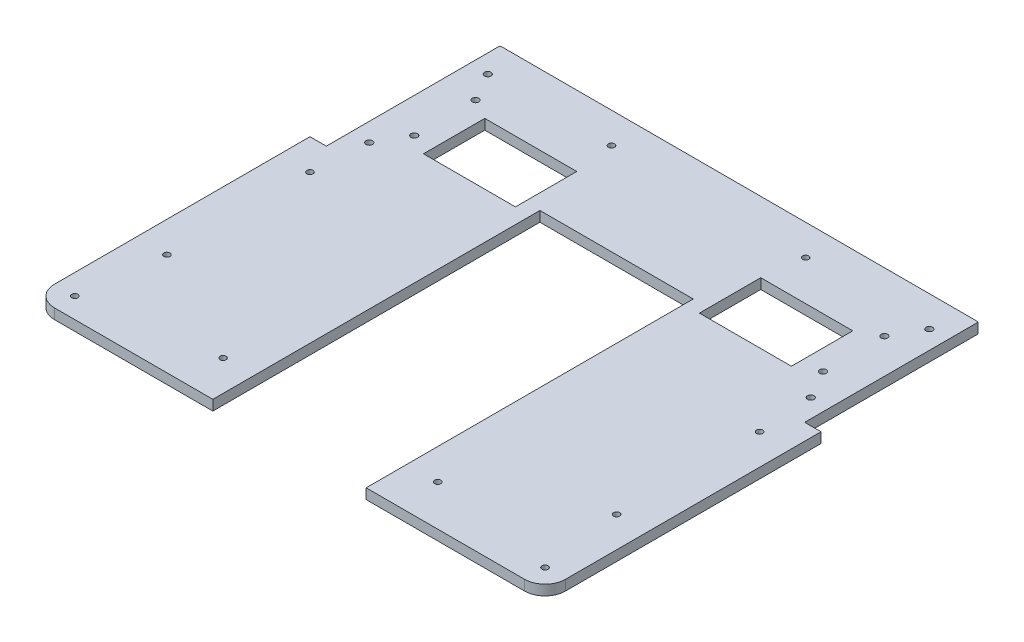
SolidWorks part; units mm, degrees
ref_plane "前视基准面" through (0, 0, 0) normal (0, 0, 1) x (1, 0, 0)
ref_plane "上视基准面" through (0, 0, 0) normal (0, 1, 0) x (1, 0, 0)
ref_plane "右视基准面" through (0, 0, 0) normal (1, 0, 0) x (0, 0, -1)
sketch "草图1" plane through (0, 0, 0) normal (0, 1, 0) x (1, 0, 0)
  line L1 (10, 0) -> (240, 0)
  line L2 (0, -10) -> (0, -210)
  line L3 (10, -220) -> (240, -220)
  line L4 (250, -10) -> (250, -210)
  arc A0 (0, -210) -> (10, -220) centre (10, -210) ccw
  arc A1 (240, -220) -> (250, -210) centre (240, -210) ccw
  arc A2 (240, 0) -> (250, -10) centre (240, -10) cw
  arc A3 (10, 0) -> (0, -10) centre (10, -10) ccw
  point P9 (250, -220)
  point P12 (250, 0)
  point P15 (0, 0)
  dimension "D3" = 10
  dimension "D1" = 250
  dimension "D2" = 220
extrude "凸台-拉伸1" add sketch "草图1" along normal blind 5
sketch "草图2" plane through (0, 0, 0) normal (0, -1, 0) x (1, 0, 0)
  line L0 (239.1778, 11.85) -> (239.1778, 76.15) construction
  line L1 (239.1778, 11.85) -> (239.1778, 76.15)
  line L2 (250, 210) -> (250, 10) construction
  line L3 (239.1778, 76.15) -> (250, 76.15)
  line L4 (239.1778, 76.15) -> (239.1778, 0)
  line L5 (239.1778, 0) -> (250, 0)
  line L6 (250, 76.15) -> (250, 0)
  line L7 (125, 220) -> (125, 0) construction
  line L8 (10, 220) -> (240, 220) construction
  line L9 (240, 0) -> (10, 0) construction
  line L10 (0, 76.15) -> (0, 0)
  line L11 (10.8222, 0) -> (0, 0)
  line L12 (10.8222, 76.15) -> (10.8222, 0)
  line L13 (10.8222, 76.15) -> (0, 76.15)
sketch "草图4" plane through (0, 0, 0) normal (0, -1, 0) x (1, 0, 0)
  line L1 (125, 0) -> (125, 220) construction
  line L2 (240, 0) -> (10, 0) construction
  line L3 (10, 220) -> (240, 220) construction
  line L8 (170, 64.475) -> (170, 34.475)
  line L16 (215, 34.475) -> (170, 34.475)
  line L17 (215, 64.475) -> (215, 34.475)
  line L18 (215, 64.475) -> (170, 64.475)
  line L19 (209.9, 64.475) -> (215, 64.475)
  line L20 (215, 64.475) -> (215, 46.825)
  line L21 (204.1, 64.475) -> (199, 64.475)
  line L22 (209.9, 64.475) -> (215, 64.475)
  line L23 (204.1, 64.475) -> (199, 64.475)
  line L24 (40.1, 64.475) -> (45.9, 64.475)
  line L25 (35, 64.475) -> (35, 46.825)
  line L26 (45.9, 64.475) -> (51, 64.475)
  line L27 (215, 64.475) -> (215, 46.825)
  line L28 (209.9, 64.475) -> (204.1, 64.475)
  line L29 (0, 10) -> (0, 210) construction
  line L30 (40.1, 64.475) -> (35, 64.475)
  line L31 (45.9, 64.475) -> (51, 64.475)
  line L33 (35, 64.475) -> (35, 46.825)
  line L35 (40.1, 64.475) -> (35, 64.475)
  line L38 (35, 64.475) -> (80, 64.475)
  line L39 (35, 64.475) -> (35, 34.475)
  line L120 (35, 34.475) -> (80, 34.475)
  line L121 (80, 64.475) -> (80, 34.475)
  dimension "D3" = 45
  dimension "D4" = 30
  dimension "D1" = 35
extrude "切除-拉伸3" cut sketch "草图4" against normal blind 5
sketch "草图5" plane through (0, 0, 0) normal (0, -1, 0) x (1, 0, 0)
  line L0 (125, 220) -> (125, 0) construction
  line L1 (10, 220) -> (240, 220) construction
  line L2 (240, 0) -> (10, 0) construction
  line L3 (87.5, 220) -> (162.5, 220) construction
  line L4 (87.5, 220) -> (87.5, 60)
  line L5 (162.5, 220) -> (87.5, 220)
  line L6 (162.5, 220) -> (162.5, 60)
  line L7 (162.5, 60) -> (87.5, 60)
  point P11 (125, 60)
  dimension "D1" = 37.5
  dimension "D2" = 160
extrude "切除-拉伸4" cut sketch "草图5" against normal blind 5
sketch "草图6" plane through (0, 0, 0) normal (0, -1, 0) x (1, 0, 0)
  line L0 (72.5, 220) -> (72.5, 200) construction
  line L1 (10, 220) -> (87.5, 220) construction
  line L2 (72.5, 200) -> (87.5, 200) construction
  line L7 (87.5, 220) -> (87.5, 60) construction
  line L8 (125, 60) -> (125, 181.8158) construction
  line L9 (87.5, 60) -> (162.5, 60) construction
  line L10 (87.5, 60) -> (87.5, 0) construction
  line L11 (240, 0) -> (10, 0) construction
  line L12 (87.5, 20) -> (92.5, 20) construction
  line L13 (92.5, 20) -> (92.5, 0) construction
  line L14 (92.5, 20) -> (107.5, 20) construction
  circle A0 centre (72.5, 200) radius 1.5
  circle A3 centre (177.5, 200) radius 1.5
  dimension "D3" = 3
  dimension "D1" = 20
  dimension "D2" = 15
  dimension "D4" = 5
  dimension "D5" = 20
  dimension "D6" = 15
extrude "切除-拉伸5" cut sketch "草图6" against normal up to next
sketch "草图7" plane through (0, 0, 0) normal (0, -1, 0) x (1, 0, 0)
  line L0 (17, 15) -> (17, 73) construction
  line L1 (25, 29) -> (25, 59) construction
  line L2 (17, 44) -> (25, 44) construction
  line L3 (240, 0) -> (10, 0) construction
  line L5 (125, 60) -> (125, 0) construction
  line L6 (87.5, 60) -> (162.5, 60) construction
  line L8 (233, 44) -> (225, 44) construction
  line L9 (225, 29) -> (225, 59) construction
  line L10 (233, 15) -> (233, 73) construction
  line L11 (0, 10) -> (0, 210) construction
  circle A0 centre (17, 15) radius 1.6
  circle A1 centre (25, 29) radius 1.6
  circle A2 centre (25, 59) radius 1.6
  circle A3 centre (17, 73) radius 1.6
  circle A4 centre (233, 73) radius 1.6
  circle A5 centre (225, 59) radius 1.6
  circle A6 centre (225, 29) radius 1.6
  circle A7 centre (233, 15) radius 1.6
  dimension "D1" = 8
  dimension "D2" = 58
  dimension "D3" = 30
  dimension "D4" = 58
  dimension "D5" = 17
  dimension "D6" = 15
extrude "切除-拉伸7" cut sketch "草图7" against normal up to next
sketch "草图8" plane through (0, 0, 0) normal (0, -1, 0) x (1, 0, 0)
  line L0 (250, 170) -> (235, 170) construction
  line L1 (250, 210) -> (250, 10) construction
  line L2 (235, 170) -> (235, 220) construction
  line L3 (162.5, 220) -> (240, 220) construction
  line L4 (235, 170) -> (235, 100) construction
  line L5 (235, 100) -> (250, 100) construction
  line L6 (125, 60) -> (125, 122.441) construction
  line L7 (87.5, 60) -> (162.5, 60) construction
  line L8 (15, 170) -> (15, 100) construction
  circle A0 centre (235, 170) radius 1.5
  circle A1 centre (235, 100) radius 1.5
  circle A2 centre (15, 100) radius 1.5
  circle A3 centre (15, 170) radius 1.5
  dimension "D4" = 3
  dimension "D5" = 3
  dimension "D1" = 15
  dimension "D2" = 50
  dimension "D3" = 70
extrude "切除-拉伸8" cut sketch "草图8" against normal up to next
sketch "草图9" plane through (0, 0, 0) normal (0, -1, 0) x (1, 0, 0)
  line L0 (87.5, 60) -> (87.5, 0) construction
  line L1 (240, 0) -> (10, 0) construction
  line L2 (87.5, 0) -> (87.5, 15) construction
  line L3 (87.5, 15) -> (77.5, 15) construction
  line L4 (10, 220) -> (10, 210) construction
  line L5 (125, 60) -> (125, 0) construction
  line L6 (87.5, 60) -> (162.5, 60) construction
  circle A0 centre (77.5, 15) radius 1.5
  circle A1 centre (10, 210) radius 1.5
  circle A2 centre (240, 210) radius 1.5
  circle A3 centre (172.5, 15) radius 1.5
  dimension "D3" = 3
  dimension "D4" = 3
  dimension "D1" = 15
  dimension "D2" = 10
extrude "切除-拉伸9" cut sketch "草图9" against normal up to next
sketch "草图10" plane through (0, 0, 0) normal (0, -1, 0) x (1, 0, 0)
  line L0 (125, 60) -> (125, 0) construction
  line L1 (0, 0) -> (8, 0)
  line L2 (0, 0) -> (0, 85)
  line L3 (0, 85) -> (8, 85)
  line L4 (8, 0) -> (8, 85)
  line L5 (87.5, 60) -> (162.5, 60) construction
  line L6 (240, 0) -> (10, 0) construction
  line L7 (242, 0) -> (242, 85)
  line L8 (250, 85) -> (242, 85)
  line L9 (250, 0) -> (250, 85)
  line L10 (250, 0) -> (242, 0)
  dimension "D1" = 8
  dimension "D2" = 85
extrude "切除-拉伸10" cut sketch "草图10" against normal up to next
